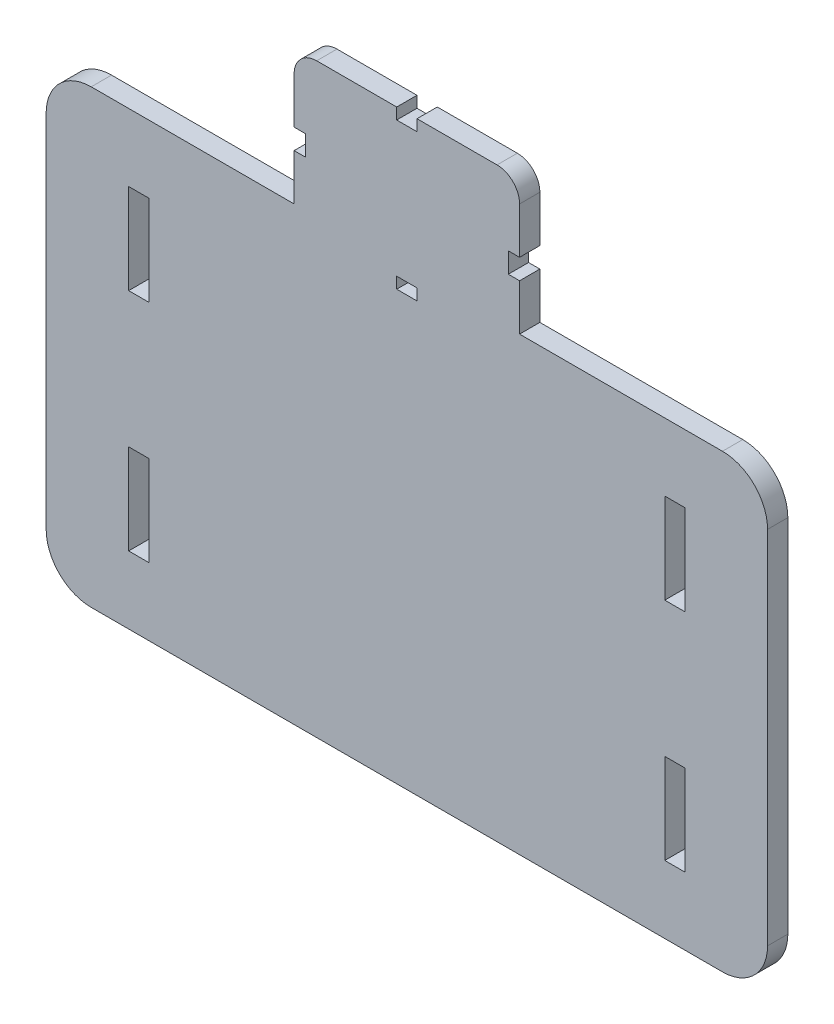
SolidWorks part; units mm, degrees
material "Balsa"
ref_plane "Front Plane" through (0, 0, 0) normal (0, 0, 1) x (1, 0, 0)
ref_plane "Top Plane" through (0, 0, 0) normal (0, 1, 0) x (1, 0, 0)
ref_plane "Right Plane" through (0, 0, 0) normal (1, 0, 0) x (0, 0, -1)
sketch "Sketch1" plane through (0, 0, 0) normal (0, 0, 1) x (1, 0, 0)
  line L1 (-80, -50) -> (80, -50)
  line L2 (-80, -50) -> (-80, 50)
  line L3 (-80, 50) -> (80, 50)
  line L4 (80, -50) -> (80, 50)
  line L5 (-80, -50) -> (80, 50) construction
  line L6 (-80, 50) -> (80, -50) construction
  point P0 (0, 0)
  dimension "D1" = 100
  dimension "160" = 160
extrude "Boss-Extrude1" add sketch "Sketch1" along normal blind 4.5
fillet "Fillet1" radius 10 4 edges at (-80, 50, 2.25) (-80, -50, 2.25) (80, -50, 2.25) (80, 50, 2.25)
sketch "Sketch2" plane through (0, 0, 4.5) normal (0, 0, 1) x (1, 0, 0)
  line L0 (70, 50) -> (-70, 50) construction
  line L1 (-61.7, 35) -> (-57.2, 35)
  line L2 (-61.7, 35) -> (-61.7, 15)
  line L3 (-61.7, 15) -> (-57.2, 15)
  line L4 (-57.2, 35) -> (-57.2, 15)
  line L5 (0, 0) -> (-19.6934, 0) construction
  line L6 (-19.6934, 0) -> (0, 0) construction
  line L7 (0, -13.1285) -> (0, 13.1285) construction
  line L8 (-57.2, -35) -> (-57.2, -15)
  line L9 (-61.7, -15) -> (-57.2, -15)
  line L10 (-61.7, -35) -> (-61.7, -15)
  line L11 (-61.7, -35) -> (-57.2, -35)
  line L12 (61.7, -35) -> (57.2, -35)
  line L13 (61.7, -35) -> (61.7, -15)
  line L14 (61.7, -15) -> (57.2, -15)
  line L15 (57.2, -35) -> (57.2, -15)
  line L16 (57.2, 35) -> (57.2, 15)
  line L17 (61.7, 15) -> (57.2, 15)
  line L18 (61.7, 35) -> (61.7, 15)
  line L19 (61.7, 35) -> (57.2, 35)
  dimension "D1" = 57.2
  dimension "D2" = 4.5
  dimension "D3" = 20
  dimension "D4" = 15
extrude "Cut-Extrude1" cut sketch "Sketch2" against normal blind 5
sketch "Sketch3" plane through (0, 0, 4.5) normal (0, 0, 1) x (1, 0, 0)
  line L0 (70, 50) -> (-70, 50) construction
  line L1 (-25, 80) -> (25, 80)
  line L2 (-25, 80) -> (-25, 50)
  line L3 (-25, 50) -> (25, 50)
  line L4 (25, 80) -> (25, 50)
  point P6 (0, 80)
  dimension "D1" = 30
  dimension "D2" = 50
extrude "Boss-Extrude2" add sketch "Sketch3" against normal blind 4.5
fillet "Fillet2" radius 5 2 edges at (25, 80, 2.25) (-25, 80, 2.25)
sketch "Sketch4" plane through (0, 0, 4.5) normal (0, 0, 1) x (1, 0, 0)
  line L0 (20, 80) -> (-20, 80) construction
  line L1 (-2.25, 82.5) -> (2.25, 82.5)
  line L2 (-2.25, 82.5) -> (-2.25, 77.5)
  line L3 (-2.25, 77.5) -> (2.25, 77.5)
  line L4 (2.25, 82.5) -> (2.25, 77.5)
  line L5 (-2.25, 82.5) -> (2.25, 77.5) construction
  line L6 (-2.25, 77.5) -> (2.25, 82.5) construction
  line L7 (-25, 62.5) -> (25, 62.5) construction
  line L8 (-25, 75) -> (-25, 50) construction
  line L9 (25, 50) -> (25, 75) construction
  line L10 (-2.25, 47.5) -> (2.25, 42.5) construction
  line L11 (-2.25, 42.5) -> (2.25, 47.5) construction
  line L12 (2.25, 42.5) -> (2.25, 47.5)
  line L13 (-2.25, 47.5) -> (2.25, 47.5)
  line L14 (-2.25, 42.5) -> (-2.25, 47.5)
  line L15 (-2.25, 42.5) -> (2.25, 42.5)
  line L16 (-2.25, 45) -> (2.25, 45) construction
  line L17 (-2.25, 45) -> (2.7814, 45)
  line L18 (-22.5, 60.25) -> (-27.5, 60.25)
  line L19 (-22.5, 60.25) -> (-22.5, 64.75)
  line L20 (-22.5, 64.75) -> (-27.5, 64.75)
  line L21 (-27.5, 60.25) -> (-27.5, 64.75)
  line L22 (-22.5, 60.25) -> (-27.5, 64.75) construction
  line L23 (-22.5, 64.75) -> (-27.5, 60.25) construction
  line L24 (22.5, 60.25) -> (27.5, 60.25)
  line L25 (22.5, 60.25) -> (22.5, 64.75)
  line L26 (22.5, 64.75) -> (27.5, 64.75)
  line L27 (27.5, 60.25) -> (27.5, 64.75)
  line L28 (22.5, 60.25) -> (27.5, 64.75) construction
  line L29 (22.5, 64.75) -> (27.5, 60.25) construction
  point P0 (0, 80)
  point P17 (0, 45)
  line M24 (25, 50) -> (25, 75)
  line M26 (20, 80) -> (-20, 80)
  line M28 (-25, 75) -> (-25, 50)
  dimension "D1" = 5
  dimension "D2" = 4.5
  dimension "D3" = 4.5
  dimension "D4" = 5
  dimension "D5" = 5
  dimension "D6" = 4.5
extrude "Cut-Extrude2" cut sketch "Sketch4" against normal blind 4.5 contours L4 L2 L3 M26 | L24 L27 L26 M24 | L26 L25 L24 M24 | L19 L20 L18 M28 | L14 L17 L12 L13
